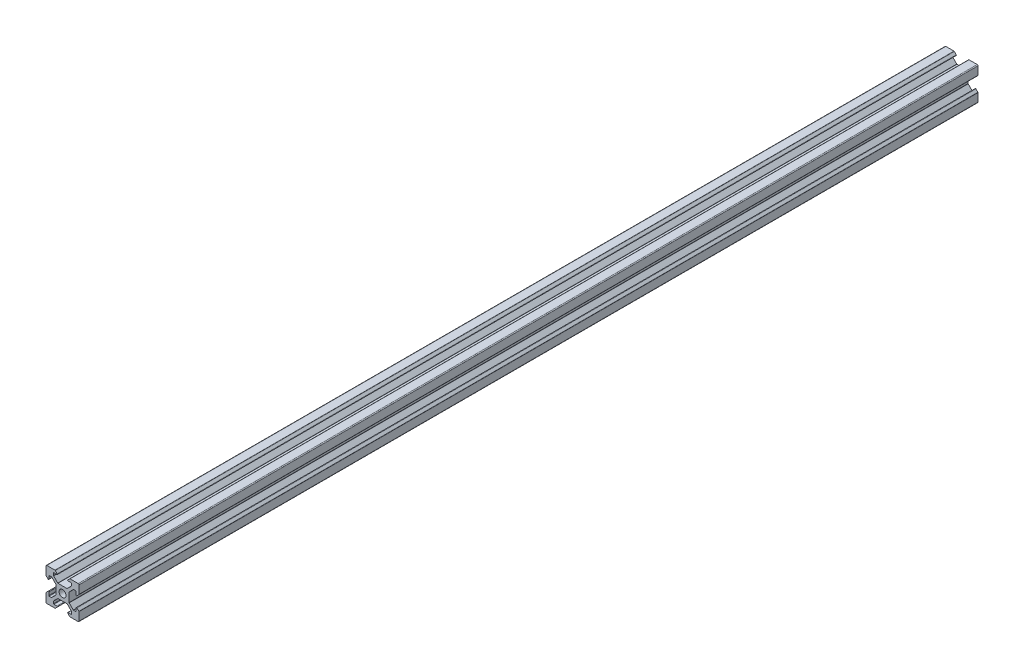
SolidWorks part; units mm, degrees
material "1060 Alloy"
ref_plane "Front Plane" through (0, 0, 0) normal (0, 0, 1) x (1, 0, 0)
ref_plane "Top Plane" through (0, 0, 0) normal (0, 1, 0) x (1, 0, 0)
ref_plane "Right Plane" through (0, 0, 0) normal (1, 0, 0) x (0, 0, -1)
sketch "Model" plane through (0, 0, 0) normal (0, 0, 1) x (1, 0, 0)
  line L0 (2012.9312, 1381.8004) -> (2012.9312, 1378.2004)
  line L1 (2016.4702, 1376.0004) -> (2017.3922, 1376.0004)
  line L2 (2020.9312, 1380.4614) -> (2020.9312, 1379.5394)
  line L3 (2016.4702, 1384.0004) -> (2017.3922, 1384.0004)
  line L270 (2012.9312, 1381.8004) -> (2012.9312, 1382.7004)
  line L271 (2012.8433, 1382.9125) -> (2010.3787, 1385.3772)
  line L272 (2010.2019, 1385.4504) -> (2008.8812, 1385.4504)
  line L273 (2008.6312, 1385.2004) -> (2008.6312, 1383.3504)
  line L274 (2008.2044, 1383.1736) -> (2007.0191, 1384.359)
  line L275 (2006.9312, 1384.5711) -> (2006.9312, 1389.5004)
  line L276 (2007.4312, 1390.0004) -> (2012.3605, 1390.0004)
  line L277 (2012.5726, 1389.9125) -> (2013.758, 1388.7272)
  line L278 (2013.5812, 1388.3004) -> (2011.7312, 1388.3004)
  line L279 (2011.4812, 1388.0504) -> (2011.4812, 1386.7297)
  line L280 (2011.5544, 1386.5529) -> (2014.0338, 1384.0736)
  line L281 (2014.2105, 1384.0004) -> (2016.4702, 1384.0004)
  line L282 (2017.3922, 1384.0004) -> (2019.6519, 1384.0004)
  line L283 (2019.8287, 1384.0736) -> (2022.308, 1386.5529)
  line L284 (2022.3812, 1386.7297) -> (2022.3812, 1388.0504)
  line L285 (2022.1312, 1388.3004) -> (2020.2812, 1388.3004)
  line L286 (2020.1044, 1388.7272) -> (2021.2898, 1389.9125)
  line L287 (2021.5019, 1390.0004) -> (2026.4312, 1390.0004)
  line L288 (2026.9312, 1389.5004) -> (2026.9312, 1384.5711)
  line L289 (2026.8433, 1384.359) -> (2025.658, 1383.1736)
  line L290 (2025.2312, 1383.3504) -> (2025.2312, 1385.2004)
  line L291 (2024.9812, 1385.4504) -> (2023.6605, 1385.4504)
  line L292 (2023.4838, 1385.3772) -> (2021.0044, 1382.8978)
  line L293 (2020.9312, 1382.7211) -> (2020.9312, 1380.4614)
  line L294 (2020.9312, 1379.5394) -> (2020.9312, 1377.2797)
  line L295 (2021.0044, 1377.1029) -> (2023.4838, 1374.6236)
  line L296 (2023.6605, 1374.5504) -> (2024.9812, 1374.5504)
  line L297 (2025.2312, 1374.8004) -> (2025.2312, 1376.6504)
  line L298 (2025.658, 1376.8272) -> (2026.8433, 1375.6418)
  line L299 (2026.9312, 1375.4297) -> (2026.9312, 1370.5004)
  line L300 (2026.4312, 1370.0004) -> (2021.5019, 1370.0004)
  line L301 (2021.2898, 1370.0883) -> (2020.1044, 1371.2736)
  line L302 (2020.2812, 1371.7004) -> (2022.1312, 1371.7004)
  line L303 (2022.3812, 1371.9504) -> (2022.3812, 1373.2711)
  line L304 (2022.308, 1373.4478) -> (2019.8287, 1375.9272)
  line L305 (2019.6519, 1376.0004) -> (2017.3922, 1376.0004)
  line L306 (2016.4702, 1376.0004) -> (2014.2105, 1376.0004)
  line L307 (2014.0338, 1375.9272) -> (2011.5544, 1373.4478)
  line L308 (2011.4812, 1373.2711) -> (2011.4812, 1371.9504)
  line L309 (2011.7312, 1371.7004) -> (2013.5812, 1371.7004)
  line L310 (2013.758, 1371.2736) -> (2012.5726, 1370.0883)
  line L311 (2012.3605, 1370.0004) -> (2007.4312, 1370.0004)
  line L312 (2006.9312, 1370.5004) -> (2006.9312, 1375.4297)
  line L313 (2007.0191, 1375.6418) -> (2008.2044, 1376.8272)
  line L314 (2008.6312, 1376.6504) -> (2008.6312, 1374.8004)
  line L315 (2008.8812, 1374.5504) -> (2010.2019, 1374.5504)
  line L316 (2010.3787, 1374.6236) -> (2012.8433, 1377.0883)
  line L317 (2012.9312, 1377.3004) -> (2012.9312, 1378.2004)
  circle A0 centre (2016.9312, 1380.0004) radius 2.1
  arc A427 (2012.9312, 1382.7004) -> (2012.8433, 1382.9125) centre (2012.6312, 1382.7004) ccw
  arc A428 (2010.3787, 1385.3772) -> (2010.2019, 1385.4504) centre (2010.2019, 1385.2004) ccw
  arc A429 (2008.8812, 1385.4504) -> (2008.6312, 1385.2004) centre (2008.8812, 1385.2004) ccw
  arc A430 (2008.2044, 1383.1736) -> (2008.6312, 1383.3504) centre (2008.3812, 1383.3504) ccw
  arc A431 (2006.9312, 1384.5711) -> (2007.0191, 1384.359) centre (2007.2312, 1384.5711) ccw
  arc A432 (2007.4312, 1390.0004) -> (2006.9312, 1389.5004) centre (2007.4312, 1389.5004) ccw
  arc A433 (2012.5726, 1389.9125) -> (2012.3605, 1390.0004) centre (2012.3605, 1389.7004) ccw
  arc A434 (2013.5812, 1388.3004) -> (2013.758, 1388.7272) centre (2013.5812, 1388.5504) ccw
  arc A435 (2011.7312, 1388.3004) -> (2011.4812, 1388.0504) centre (2011.7312, 1388.0504) ccw
  arc A436 (2011.4812, 1386.7297) -> (2011.5544, 1386.5529) centre (2011.7312, 1386.7297) ccw
  arc A437 (2014.0338, 1384.0736) -> (2014.2105, 1384.0004) centre (2014.2105, 1384.2504) ccw
  arc A441 (2019.6519, 1384.0004) -> (2019.8287, 1384.0736) centre (2019.6519, 1384.2504) ccw
  arc A442 (2022.308, 1386.5529) -> (2022.3812, 1386.7297) centre (2022.1312, 1386.7297) ccw
  arc A443 (2022.3812, 1388.0504) -> (2022.1312, 1388.3004) centre (2022.1312, 1388.0504) ccw
  arc A444 (2020.1044, 1388.7272) -> (2020.2812, 1388.3004) centre (2020.2812, 1388.5504) ccw
  arc A445 (2021.5019, 1390.0004) -> (2021.2898, 1389.9125) centre (2021.5019, 1389.7004) ccw
  arc A446 (2026.9312, 1389.5004) -> (2026.4312, 1390.0004) centre (2026.4312, 1389.5004) ccw
  arc A447 (2026.8433, 1384.359) -> (2026.9312, 1384.5711) centre (2026.6312, 1384.5711) ccw
  arc A448 (2025.2312, 1383.3504) -> (2025.658, 1383.1736) centre (2025.4812, 1383.3504) ccw
  arc A449 (2025.2312, 1385.2004) -> (2024.9812, 1385.4504) centre (2024.9812, 1385.2004) ccw
  arc A450 (2023.6605, 1385.4504) -> (2023.4838, 1385.3772) centre (2023.6605, 1385.2004) ccw
  arc A451 (2021.0044, 1382.8978) -> (2020.9312, 1382.7211) centre (2021.1812, 1382.7211) ccw
  arc A455 (2020.9312, 1377.2797) -> (2021.0044, 1377.1029) centre (2021.1812, 1377.2797) ccw
  arc A456 (2023.4838, 1374.6236) -> (2023.6605, 1374.5504) centre (2023.6605, 1374.8004) ccw
  arc A457 (2024.9812, 1374.5504) -> (2025.2312, 1374.8004) centre (2024.9812, 1374.8004) ccw
  arc A458 (2025.658, 1376.8272) -> (2025.2312, 1376.6504) centre (2025.4812, 1376.6504) ccw
  arc A459 (2026.9312, 1375.4297) -> (2026.8433, 1375.6418) centre (2026.6312, 1375.4297) ccw
  arc A460 (2026.4312, 1370.0004) -> (2026.9312, 1370.5004) centre (2026.4312, 1370.5004) ccw
  arc A461 (2021.2898, 1370.0883) -> (2021.5019, 1370.0004) centre (2021.5019, 1370.3004) ccw
  arc A462 (2020.2812, 1371.7004) -> (2020.1044, 1371.2736) centre (2020.2812, 1371.4504) ccw
  arc A463 (2022.1312, 1371.7004) -> (2022.3812, 1371.9504) centre (2022.1312, 1371.9504) ccw
  arc A464 (2022.3812, 1373.2711) -> (2022.308, 1373.4478) centre (2022.1312, 1373.2711) ccw
  arc A465 (2019.8287, 1375.9272) -> (2019.6519, 1376.0004) centre (2019.6519, 1375.7504) ccw
  arc A469 (2014.2105, 1376.0004) -> (2014.0338, 1375.9272) centre (2014.2105, 1375.7504) ccw
  arc A470 (2011.5544, 1373.4478) -> (2011.4812, 1373.2711) centre (2011.7312, 1373.2711) ccw
  arc A471 (2011.4812, 1371.9504) -> (2011.7312, 1371.7004) centre (2011.7312, 1371.9504) ccw
  arc A472 (2013.758, 1371.2736) -> (2013.5812, 1371.7004) centre (2013.5812, 1371.4504) ccw
  arc A473 (2012.3605, 1370.0004) -> (2012.5726, 1370.0883) centre (2012.3605, 1370.3004) ccw
  arc A474 (2006.9312, 1370.5004) -> (2007.4312, 1370.0004) centre (2007.4312, 1370.5004) ccw
  arc A475 (2007.0191, 1375.6418) -> (2006.9312, 1375.4297) centre (2007.2312, 1375.4297) ccw
  arc A476 (2008.6312, 1376.6504) -> (2008.2044, 1376.8272) centre (2008.3812, 1376.6504) ccw
  arc A477 (2008.6312, 1374.8004) -> (2008.8812, 1374.5504) centre (2008.8812, 1374.8004) ccw
  arc A478 (2010.2019, 1374.5504) -> (2010.3787, 1374.6236) centre (2010.2019, 1374.8004) ccw
  arc A479 (2012.8433, 1377.0883) -> (2012.9312, 1377.3004) centre (2012.6312, 1377.3004) ccw
extrude "Boss-Extrude1" add sketch "Model" along normal blind 545
